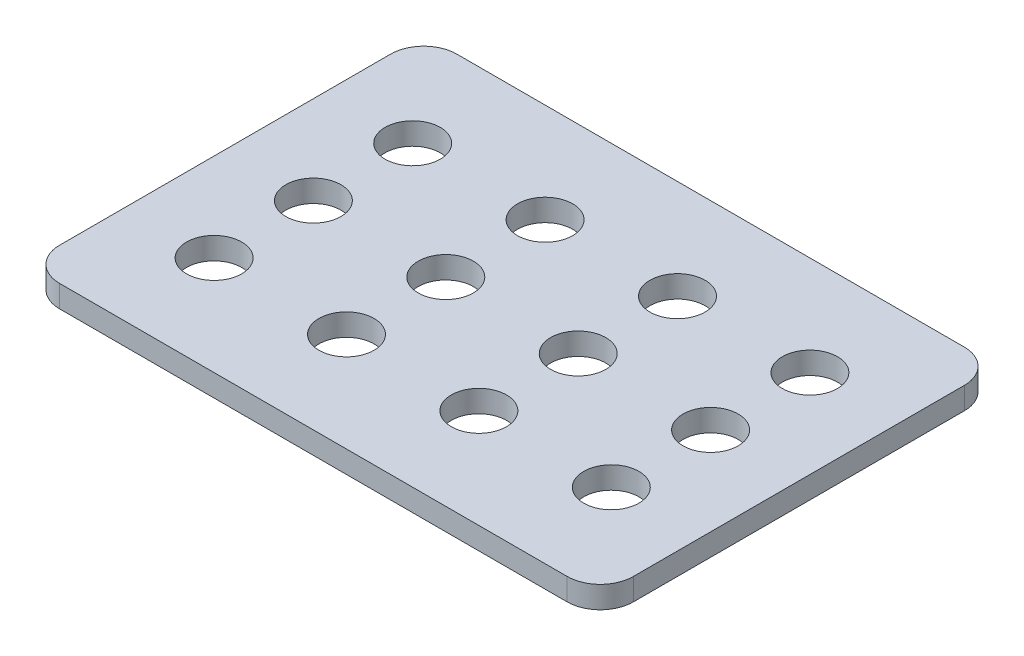
SolidWorks part; units mm, degrees
ref_plane "Front Plane" through (0, 0, 0) normal (0, 0, 1) x (1, 0, 0)
ref_plane "Top Plane" through (0, 0, 0) normal (0, 1, 0) x (1, 0, 0)
ref_plane "Right Plane" through (0, 0, 0) normal (1, 0, 0) x (0, 0, -1)
sketch "Sketch1" plane through (0, 0, 0) normal (0, 1, 0) x (1, 0, 0)
  line L0 (0, 15) -> (0, 165)
  line L1 (15, 180) -> (245, 180)
  line L2 (15, 0) -> (245, 0)
  line L3 (130, 0) -> (130, 180)
  line L4 (130, 208.4323) -> (130, -112.785) construction
  line L5 (260, 15) -> (260, 165)
  arc A0 (15, 180) -> (0, 165) centre (15, 165) ccw
  arc A1 (15, 0) -> (0, 15) centre (15, 15) cw
  circle A4 centre (40, 135) radius 12.5
  circle A5 centre (100, 135) radius 12.5
  circle A6 centre (100, 90) radius 12.5
  circle A7 centre (40, 90) radius 12.5
  circle A8 centre (40, 45) radius 12.5
  circle A9 centre (100, 45) radius 12.5
  circle A10 centre (160, 45) radius 12.5
  circle A11 centre (220, 45) radius 12.5
  circle A12 centre (220, 90) radius 12.5
  circle A13 centre (160, 90) radius 12.5
  circle A14 centre (160, 135) radius 12.5
  circle A15 centre (220, 135) radius 12.5
  arc A16 (245, 0) -> (260, 15) centre (245, 15) ccw
  arc A17 (245, 180) -> (260, 165) centre (245, 165) cw
  point P7 (0, 180)
  point P10 (0, 0)
  point P43 (260, 0)
  point P44 (260, 180)
  dimension "D3" = 15
  dimension "D4" = 15
  dimension "D6" = 45
  dimension "D8" = 60
  dimension "D5" = 25
  dimension "D1" = 130
  dimension "D2" = 180
  dimension "D7" = 40
  dimension "D9" = 45
  dimension "D10" = 45
extrude "Boss-Extrude4" add sketch "Sketch1" along normal blind 10 contours A1 L2 L3 L1 A0 L0 A9 A8 A7 A6 A5 A4 | A17 L1 L3 L2 A16 L5 A14 A12 A10 A11 A13 A15
